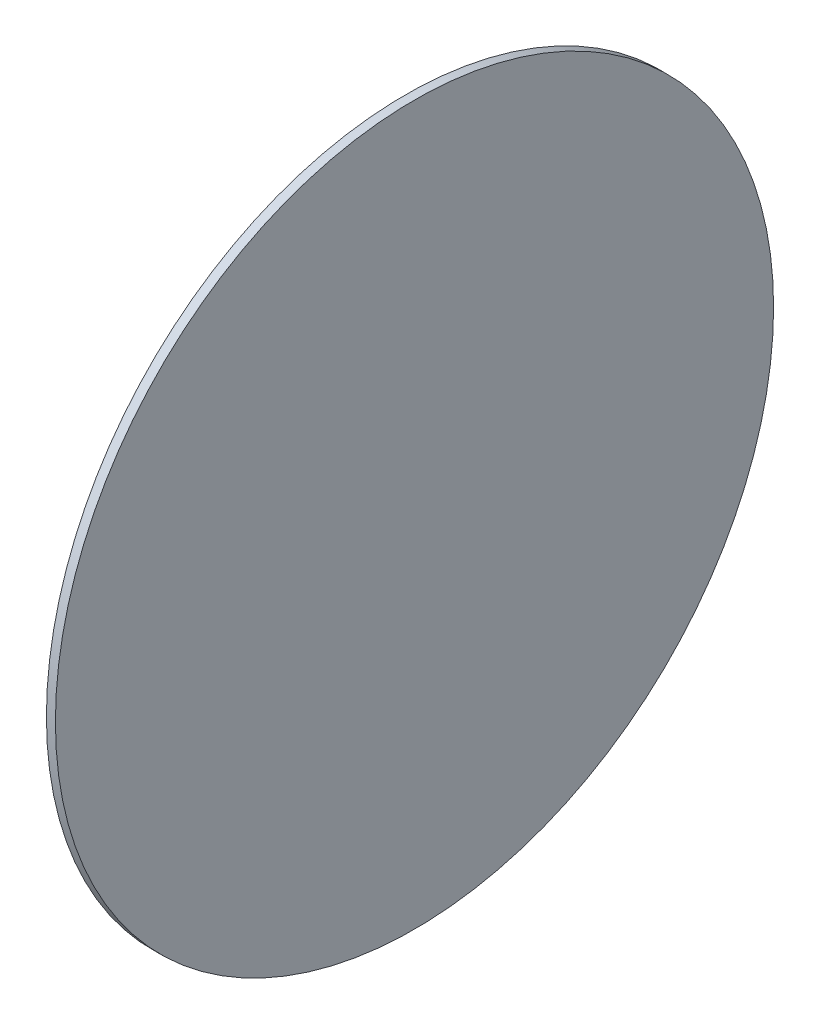
SolidWorks part; units mm, degrees
ref_plane "Alzado" through (0, 0, 0) normal (0, 0, 1) x (1, 0, 0)
ref_plane "Planta" through (0, 0, 0) normal (0, 1, 0) x (1, 0, 0)
ref_plane "Vista lateral" through (0, 0, 0) normal (1, 0, 0) x (0, 0, -1)
sketch "Croquis1" plane through (0, 0, 0) normal (1, 0, 0) x (0, 0, -1)
  line L0 (-100.8938, -17.44) -> (-91.625, -17.44) construction
  line L1 (70, 74.7242) -> (70, 61.6384) construction
  circle A0 centre (0, 0) radius 93.27 construction
  circle A1 centre (0, 0) radius 102.39 construction
  circle A2 centre (0, 0) radius 99.83
  dimension "D2" = 93.27
  dimension "D1" = 9.12
  dimension "D3" = 70
  dimension "D4" = 17.44
  dimension "D5" = 2.56
extrude "Saliente-Extruir6" add sketch "Croquis1" along normal blind 2.5
equation "\"D1@Croquis1\"= ( ( \"GROSOR_PARED_IMPRESION\" + \"TOLERANCIA\" ) * 2 ) + \"policarbonato\""
equation "\"venesta\"= 4'grosor de la venesta"
equation "\"policarbonato\"= 4'grosor del policarbonato"
equation "\"carton_trupan\"= 3'grosor del carton trupan caso laser"
equation "\"ancho_tot\"= 310'ancho tot sin llantas"
equation "\"largo_tot\"= 400'largo tot sin camera"
equation "\"alto_estimado\"= 300'alto estimado sin lidar"
equation "\"altoparaqpaselabotella\"= 75'alto estimado para que encaje la botella"
equation "\"alturaruedaloca\"= 22"
equation "\"anchoruedaloca\"= 35"
equation "\"anchopiso1motorybaterias\"= 150"
equation "\"dist-pisorampa\"= 5"
equation "\"anchoultimopiso\"= 170"
equation "\"paredtrasera\"= 100"
equation "\"agarradorcanasta\"= 275'recolector"
equation "\"alturapiso1y2\"= 80"
equation "\"alturapiso2y3\"= 80"
equation "\"GROSOR_PARED_IMPRESION\"=2.5"
equation "\"TOLERANCIA\"= 0.06"
equation "\"apertura\"= 70"
equation "\"D2@Croquis1\"= ( 4 - 0.02 ) + ( \"TOLERANCIA\" * 2 ) + 89.17"
equation "\"D4@Croquis1\"= 17.5 - \"TOLERANCIA\""
equation "\"¡\"=160"
equation "\"D5@Croquis1\"=\"GROSOR_PARED_IMPRESION\"+\"TOLERANCIA\""
